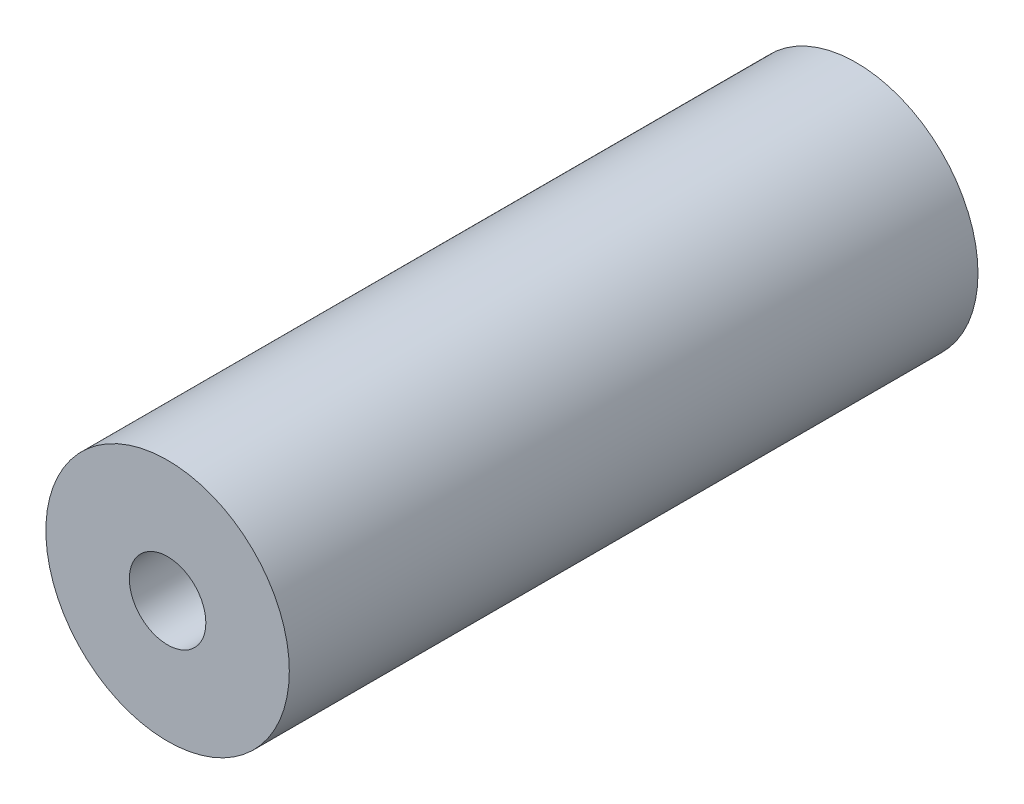
SolidWorks part; units mm, degrees
ref_plane "Front Plane" through (0, 0, 0) normal (0, 0, 1) x (1, 0, 0)
ref_plane "Top Plane" through (0, 0, 0) normal (0, 1, 0) x (1, 0, 0)
ref_plane "Right Plane" through (0, 0, 0) normal (1, 0, 0) x (0, 0, -1)
sketch "Sketch1" plane through (0, 0, 0) normal (0, 0, 1) x (1, 0, 0)
  circle A0 centre (0, 0) radius 17.5
  dimension "D1" = 35
extrude "Boss-Extrude1" add sketch "Sketch1" along normal blind 99
sketch "Sketch2" plane through (0, 0, 99) normal (0, 0, 1) x (1, 0, 0)
  circle A0 centre (0, 0) radius 2.5
  dimension "D1" = 5
extrude "Cut-Extrude1" cut sketch "Sketch2" against normal through all
sketch "Sketch3" plane through (0, 0, 99) normal (0, 0, 1) x (1, 0, 0)
  circle A0 centre (0, 0) radius 5.5
  dimension "D1" = 11
extrude "Cut-Extrude2" cut sketch "Sketch3" against normal blind 94
